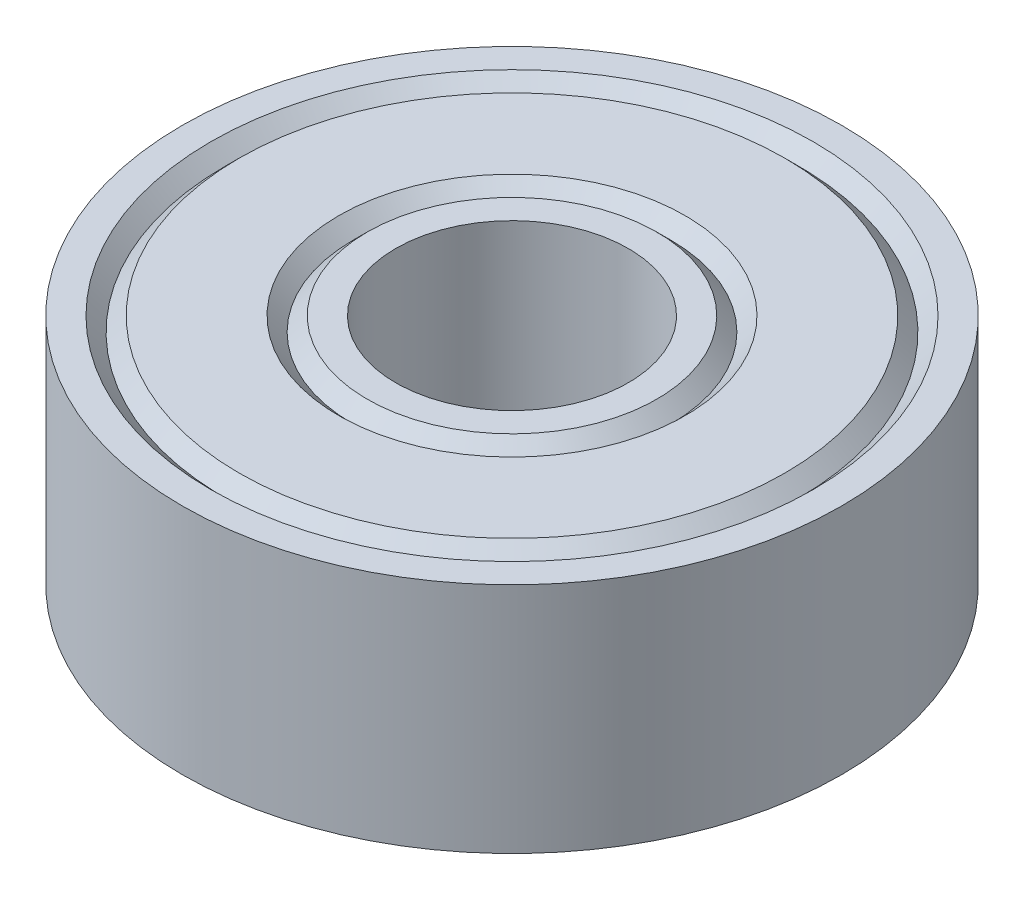
SolidWorks part; units mm, degrees
ref_plane "Front Plane" through (0, 0, 0) normal (0, 0, 1) x (1, 0, 0)
ref_plane "Top Plane" through (0, 0, 0) normal (0, 1, 0) x (1, 0, 0)
ref_plane "Right Plane" through (0, 0, 0) normal (1, 0, 0) x (0, 0, -1)
sketch "Sketch1" plane through (0, 0, 0) normal (0, 0, 1) x (1, 0, 0)
  line L0 (0, 3) -> (0, -3) construction
  line L1 (-3, 3) -> (-3.7333, 3)
  line L2 (-3, 3) -> (-3, -3)
  line L3 (-3, -3) -> (-3.7333, -3)
  line L4 (-8.5, 3) -> (-8.5, -3)
  line L5 (-7.7667, 3) -> (-7.4, 2.6333)
  line L6 (-7.4, 2.6333) -> (-7.0333, 3)
  line L7 (-4.4667, 3) -> (-4.1, 2.6333)
  line L8 (-4.1, 2.6333) -> (-3.7333, 3)
  line L9 (-7.7667, -3) -> (-7.4, -2.6333)
  line L10 (-7.4, -2.6333) -> (-7.0333, -3)
  line L11 (-4.4667, -3) -> (-4.1, -2.6333)
  line L12 (-4.1, -2.6333) -> (-3.7333, -3)
  line L13 (-4.4667, -3) -> (-7.0333, -3)
  line L14 (-7.7667, -3) -> (-8.5, -3)
  line L15 (-7.7667, 3) -> (-8.5, 3)
  line L16 (-4.4667, 3) -> (-7.0333, 3)
  line L17 (-7.4, 2.6333) -> (-4.1, 2.6333) construction
  line L18 (-7.4, 2.6333) -> (-7.4, -2.6333) construction
  line L19 (-4.1, -2.6333) -> (-7.4, -2.6333) construction
  line L20 (-4.1, 2.6333) -> (-4.1, -2.6333) construction
  line L21 (-7.4, 0) -> (-6.3, 0) construction
  line L22 (-3.7333, 3) -> (-4.4667, 3) construction
  line L23 (-6.3, 0) -> (-5.2, 0) construction
  line L24 (-7.4, 0) -> (-8.5, 0) construction
  line L25 (-5.2, 0) -> (-4.1, 0) construction
  line L26 (-4.1, 0) -> (-3, 0) construction
  dimension "D1" = 6
  dimension "D2" = 6
  dimension "D3" = 17
revolve "Revolve1" add sketch "Sketch1" angle 360 about L0
